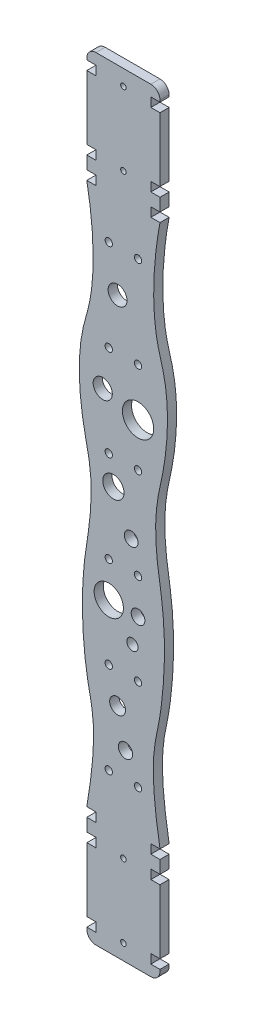
SolidWorks part; units mm, degrees
ref_plane "Plan de face" through (0, 0, 0) normal (0, 0, 1) x (1, 0, 0)
ref_plane "Plan de dessus" through (0, 0, 0) normal (0, 1, 0) x (1, 0, 0)
ref_plane "Plan de droite" through (0, 0, 0) normal (1, 0, 0) x (0, 0, -1)
sketch "Esquisse1" plane through (0, 0, 0) normal (0, 0, 1) x (1, 0, 0)
  line L0 (-20, 0) -> (20, 0)
  line L1 (20, 0) -> (20, 6)
  line L2 (20, 6) -> (15, 6)
  line L3 (15, 6) -> (15, 11)
  line L4 (15, 11) -> (20, 11)
  line L5 (8, 336.225) -> (8, 86.225) construction
  line L6 (19.9335, 46) -> (15, 46)
  line L7 (15, 46) -> (15, 51)
  line L8 (15, 51) -> (20, 51)
  line L9 (20, 51) -> (20, 58)
  line L10 (20, 58) -> (-20, 58) construction
  line L11 (-20, 58) -> (-20, 51)
  line L12 (-20, 51) -> (-15, 51)
  line L13 (-15, 51) -> (-15, 46)
  line L14 (-15, 46) -> (-19.9335, 46)
  line L16 (-20, 11) -> (-15, 11)
  line L17 (-15, 11) -> (-15, 6)
  line L18 (-15, 6) -> (-20, 6)
  line L19 (-20, 6) -> (-20, 0)
  line L20 (0, 0) -> (0, 58) construction
  line L21 (-15, 8.5) -> (15, 8.5) construction
  line L22 (15, 48.5) -> (-15, 48.5) construction
  line L23 (-20, 28.5) -> (20, 28.5) construction
  line L24 (-20, 58) -> (-15, 58)
  line L25 (-15, 58) -> (-15, 63)
  line L26 (-15, 63) -> (-20, 63)
  line L27 (-20, 63) -> (-20, 359.45) construction
  line L28 (15, 58) -> (15, 63)
  line L29 (15, 63) -> (20, 63)
  line L30 (20, 63) -> (20, 359.45) construction
  line L31 (20, 58) -> (15, 58)
  line L32 (-20, 211.225) -> (20, 211.225) construction
  line L33 (-15, 359.45) -> (-20, 359.45)
  line L34 (-15, 364.45) -> (-15, 359.45)
  line L35 (-20, 364.45) -> (-15, 364.45)
  line L36 (-20, 364.45) -> (-20, 371.45)
  line L37 (-20, 371.45) -> (-15, 371.45)
  line L38 (-15, 371.45) -> (-15, 376.45)
  line L39 (-15, 376.45) -> (-19.9335, 376.45)
  line L40 (-19.9335, 376.45) -> (-20, 411.45) construction
  line L41 (-20, 411.45) -> (-15, 411.45)
  line L42 (-15, 411.45) -> (-15, 416.45)
  line L43 (-15, 416.45) -> (-20, 416.45)
  line L44 (-20, 416.45) -> (-20, 422.45)
  line L45 (-20, 422.45) -> (20, 422.45)
  line L46 (20, 422.45) -> (20, 416.45)
  line L47 (20, 416.45) -> (15, 416.45)
  line L48 (15, 416.45) -> (15, 411.45)
  line L49 (15, 411.45) -> (20, 411.45)
  line L50 (20, 411.45) -> (19.9335, 376.45) construction
  line L51 (19.9335, 376.45) -> (15, 376.45)
  line L52 (15, 376.45) -> (15, 371.45)
  line L53 (15, 371.45) -> (20, 371.45)
  line L54 (20, 371.45) -> (20, 364.45)
  line L55 (20, 364.45) -> (15, 364.45)
  line L56 (15, 364.45) -> (15, 359.45)
  line L57 (15, 359.45) -> (20, 359.45)
  line L58 (-20, 411.45) -> (-19.9335, 376.45)
  line L63 (0, 413.95) -> (0, 373.95) construction
  line L68 (20, 411.45) -> (19.9335, 376.45)
  line L69 (-20, 11) -> (-19.9335, 46)
  line L77 (20, 11) -> (19.9335, 46)
  circle A0 centre (0, 48.5) radius 1.5
  circle A1 centre (0, 8.5) radius 1.5
  circle A2 centre (0, 29) radius 4.25 construction
  circle A3 centre (-20, 28.5) radius 1.6 construction
  circle A4 centre (20, 28.5) radius 1.6 construction
  circle A5 centre (0, 413.95) radius 1.5
  circle A6 centre (0, 373.95) radius 1.5
  circle A7 centre (0, 393.45) radius 4.25 construction
  circle A8 centre (-8, 336.225) radius 2
  circle A9 centre (8, 336.225) radius 2
  circle A10 centre (8, 286.225) radius 2
  circle A11 centre (-8, 286.225) radius 2
  circle A12 centre (8, 236.225) radius 2
  circle A13 centre (-8, 236.225) radius 2
  circle A14 centre (8, 186.225) radius 2
  circle A15 centre (-8, 186.225) radius 2
  circle A16 centre (8, 136.225) radius 2
  circle A17 centre (-8, 136.225) radius 2
  circle A18 centre (8, 86.225) radius 2
  circle A19 centre (-8, 86.225) radius 2
  circle A20 centre (-11.2994, 265.2826) radius 5.2291
  circle A21 centre (8, 260.0535) radius 8.552
  circle A22 centre (-3.1858, 313.5586) radius 5.1582
  circle A23 centre (-8, 166.8645) radius 8
  circle A24 centre (4.9278, 152.26) radius 3.0722
  circle A25 centre (8, 166.8645) radius 3.7433
  circle A26 centre (-3.1858, 119.1565) radius 4.3221
  circle A27 centre (1.1364, 100.1707) radius 3.9145
  circle A28 centre (4.2567, 201.9153) radius 3.7433
  circle A29 centre (-5.4711, 221.7141) radius 5.8199
  spline S0 degree 3 poles (-20, 359.45) (-16.0791, 338.9942) (-15.0617, 311.0526) (-26.221, 277.411) (-23.5716, 249.2865) (-16.8947, 221.6432) (-17.3203, 203.5738) (-23.1795, 169.5258) (-22.7157, 143.838) (-18.097, 113.3481) (-13.5129, 101.0525) (-20, 63) knots 0 0 0 0 0.15487 0.194994 0.378325 0.421485 0.583434 0.627025 0.813801 0.853433 1 1 1 1
  spline S1 degree 3 poles (20, 359.45) (16.0791, 338.9942) (15.0617, 311.0526) (26.221, 277.411) (23.5716, 249.2865) (16.8947, 221.6432) (17.3203, 203.5738) (23.1795, 169.5258) (22.7157, 143.838) (18.097, 113.3481) (13.5129, 101.0525) (20, 63) knots 0 0 0 0 0.15487 0.194994 0.378325 0.421485 0.583434 0.627025 0.813801 0.853433 1 1 1 1
  dimension "D6" = 3
  dimension "D7" = 3
  dimension "D8" = 8.5
  dimension "D10" = 3.2
  dimension "D12" = 7
  dimension "D9" = 4
  dimension "D1" = 5
  dimension "D2" = 30
  dimension "D3" = 40
  dimension "D4" = 6
  dimension "D5" = 40
  dimension "D11" = 20
  dimension "D13" = 296.45
  dimension "D14" = 125
  dimension "D15" = 16
  dimension "D17" = 50
  dimension "D16" = 6
extrude "Boss.-Extru.1" add sketch "Esquisse1" along normal blind 5
fillet "Congé1" radius 5 4 edges at (20, 0, 2.5) (-20, 0, 2.5) (-20, 422.45, 2.5) (20, 422.45, 2.5)
